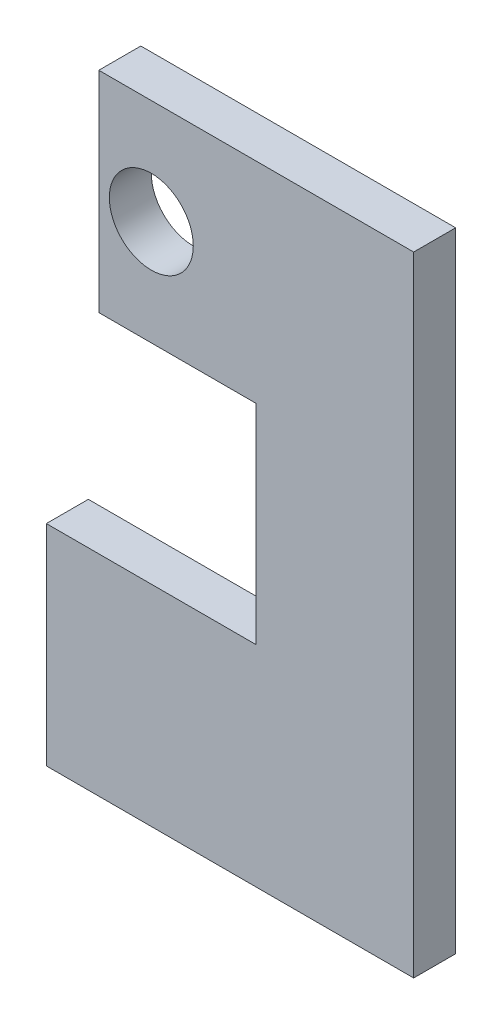
SolidWorks part; units mm, degrees
ref_plane "Front Plane" through (0, 0, 0) normal (0, 0, 1) x (1, 0, 0)
ref_plane "Top Plane" through (0, 0, 0) normal (0, 1, 0) x (1, 0, 0)
ref_plane "Right Plane" through (0, 0, 0) normal (1, 0, 0) x (0, 0, -1)
sketch "Sketch1" plane through (0, 0, 0) normal (0, 0, 1) x (1, 0, 0)
  line L0 (0, -50) -> (0, -149.537)
  line L1 (-75, 50) -> (75, 50)
  line L2 (-75, 50) -> (-75, -50)
  line L3 (-75, -50) -> (0, -50)
  line L4 (75, 50) -> (75, -50)
  line L5 (0, -149.537) -> (-100, -149.537)
  line L6 (-100, -149.537) -> (-100, -249.537)
  line L7 (-100, -249.537) -> (75, -249.537)
  line L8 (75, -249.537) -> (75, -50)
  circle A0 centre (-50, 0) radius 20
  dimension "D5" = 40
  dimension "D1" = 100
  dimension "D2" = 150
  dimension "D3" = 75
  dimension "D4" = 50
  dimension "D6" = 25
  dimension "D7" = 75
  dimension "D8" = 100
  dimension "D9" = 100
extrude "Boss-Extrude2" add sketch "Sketch1" along normal blind 20
